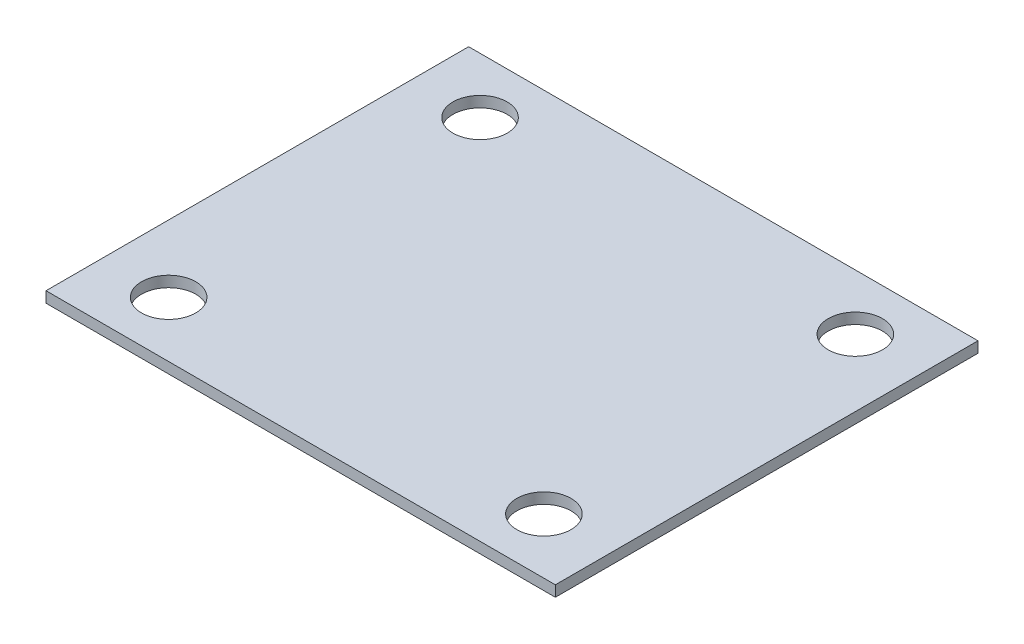
SolidWorks part; units mm, degrees
ref_plane "Front Plane" through (0, 0, 0) normal (0, 0, 1) x (1, 0, 0)
ref_plane "Top Plane" through (0, 0, 0) normal (0, 1, 0) x (1, 0, 0)
ref_plane "Right Plane" through (0, 0, 0) normal (1, 0, 0) x (0, 0, -1)
sketch "Sketch1" plane through (0, 0, 0) normal (0, 1, 0) x (1, 0, 0)
  line L1 (-23.5, 19.5) -> (23.5, 19.5)
  line L2 (-23.5, 19.5) -> (-23.5, -19.5)
  line L3 (-23.5, -19.5) -> (23.5, -19.5)
  line L4 (23.5, 19.5) -> (23.5, -19.5)
  line L5 (-23.5, 19.5) -> (23.5, -19.5) construction
  line L6 (-23.5, -19.5) -> (23.5, 19.5) construction
  point P0 (0, 0)
  dimension "D1" = 39
  dimension "D2" = 47
extrude "Boss-Extrude1" add sketch "Sketch1" along normal blind 1 contours L1 L4 L3 L2
sketch "Sketch2" plane through (0, 1, 0) normal (0, 1, 0) x (1, 0, 0)
  line L0 (-23.5, 19.5) -> (23.5, -19.5) construction
  line L1 (23.5, -19.5) -> (23.5, 19.5) construction
  line L2 (-23.5, -19.5) -> (23.5, 19.5) construction
  line L3 (-17.3151, -14.3679) -> (17.3151, 14.3679) construction
  circle A0 centre (-17.3151, 14.3679) radius 2.5
  circle A1 centre (17.3151, -14.3679) radius 2.5
  circle A4 centre (17.3151, 14.3679) radius 2.5
  circle A5 centre (-17.3151, -14.3679) radius 2.5
  point P15 (0, 0)
  point P17 (0, 0)
  dimension "D1" = 22.5
  dimension "D2" = 5
  dimension "D3" = 45
  dimension "D4" = 5
  dimension "D5" = 5
  dimension "D7" = 5
  dimension "D6" = 45
extrude "Cut-Extrude1" cut sketch "Sketch2" against normal through all
